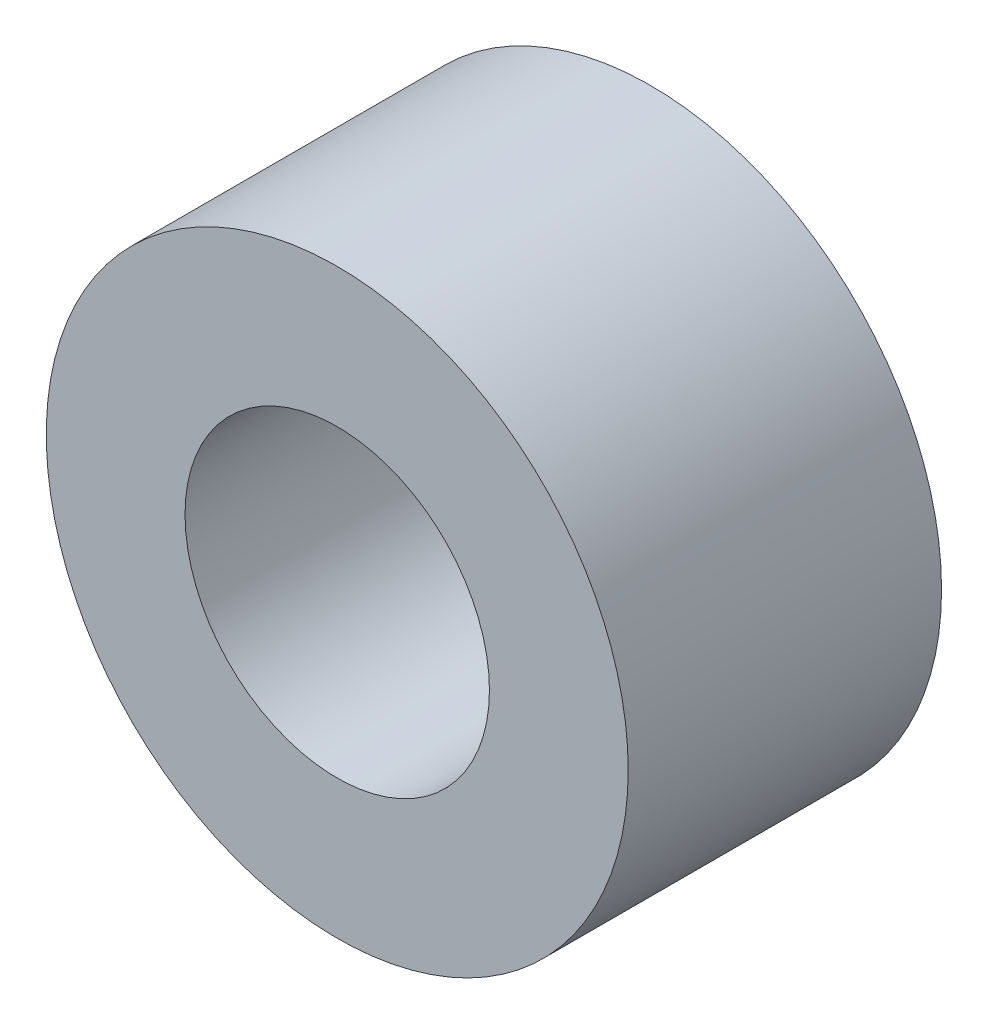
SolidWorks part; units mm, degrees
material "ABS"
ref_plane "前视基准面" through (0, 0, 0) normal (0, 0, 1) x (1, 0, 0)
ref_plane "上视基准面" through (0, 0, 0) normal (0, 1, 0) x (1, 0, 0)
ref_plane "右视基准面" through (0, 0, 0) normal (1, 0, 0) x (0, 0, -1)
sketch "草图1" plane through (0, 0, 0) normal (0, 0, 1) x (1, 0, 0)
  circle A0 centre (0, 0) radius 1.7
  circle A1 centre (0, 0) radius 3.25
  dimension "D1" = 3.4
  dimension "D2" = 6.5
extrude "凸台-拉伸1" add sketch "草图1" along normal blind 3.5
